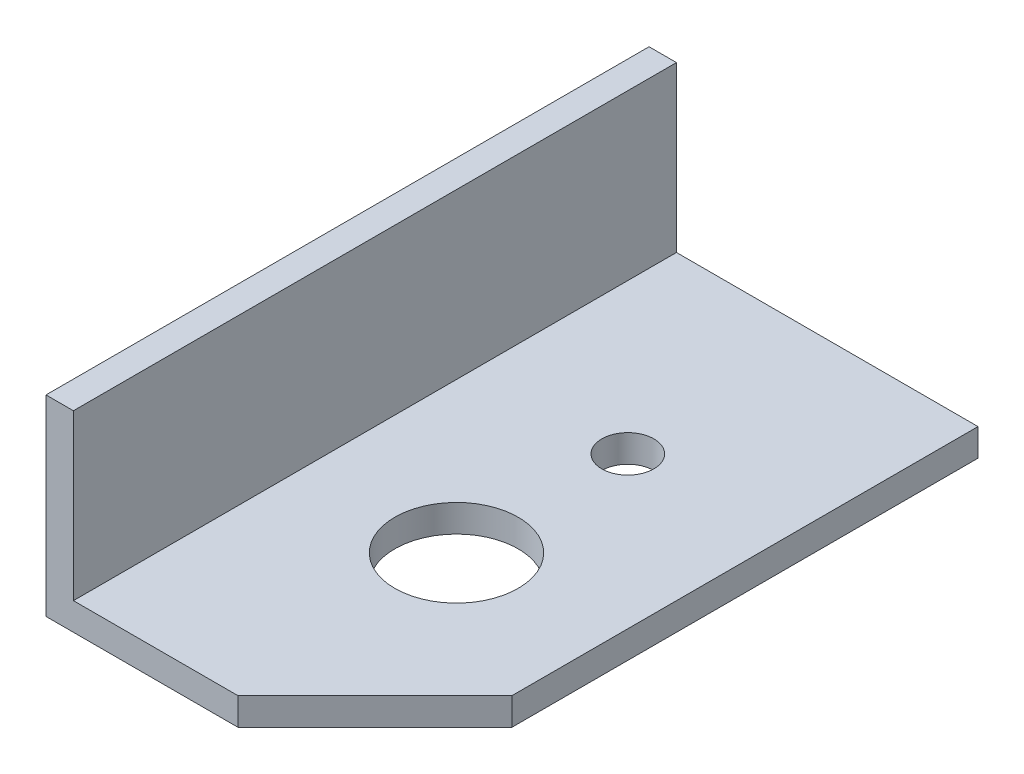
SolidWorks part; units mm, degrees
ref_plane "Спереди" through (0, 0, 0) normal (0, 0, 1) x (1, 0, 0)
ref_plane "Сверху" through (0, 0, 0) normal (0, 1, 0) x (1, 0, 0)
ref_plane "Справа" through (0, 0, 0) normal (1, 0, 0) x (0, 0, -1)
sketch "Эскиз2" plane through (0, 0, 0) normal (0, 0, 1) x (1, 0, 0)
  line L0 (0, 0) -> (0, 14)
  line L1 (0, 0) -> (24, 0)
extrude "Вытянуть-Тонкостенный1" add sketch "Эскиз2" along normal blind 44 thin
sketch "Эскиз4" plane through (0, 2, 0) normal (0, 1, 0) x (-1, 0, 0)
  circle A0 centre (-12.95, 14.5) radius 1.9
  circle A1 centre (-12.95, 27) radius 4.5
extrude "Вырез-Вытянуть1" cut sketch "Эскиз4" against normal through all
chamfer "Фаска1" distance 10 angle 45 1 edges at (24, 1, 44)
